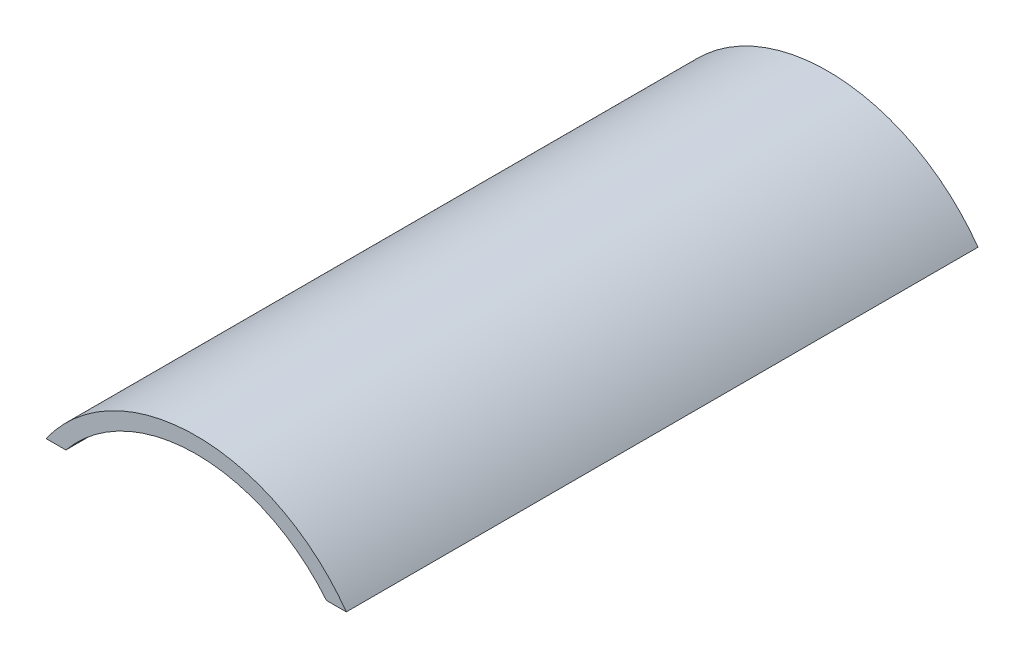
SolidWorks part; units mm, degrees
ref_plane "Front Plane" through (0, 0, 0) normal (0, 0, 1) x (1, 0, 0)
ref_plane "Top Plane" through (0, 0, 0) normal (0, 1, 0) x (1, 0, 0)
ref_plane "Right Plane" through (0, 0, 0) normal (1, 0, 0) x (0, 0, -1)
sketch "Sketch1" plane through (0, 0, 0) normal (0, 0, 1) x (1, 0, 0)
  line L2 (-12.3765, 10.1401) -> (-14.2628, 10.1401)
  line L3 (12.3765, 10.1401) -> (14.2628, 10.1401)
  line L5 (-15.2184, 8.6401) -> (15.2184, 8.6401) construction
  line L6 (-12.3765, 10.1401) -> (12.3765, 10.1401) construction
  arc A0 (12.3765, 10.1401) -> (-12.3765, 10.1401) centre (0, 0) ccw
  arc A1 (14.2628, 10.1401) -> (-14.2628, 10.1401) centre (0, 0) ccw
  arc A2 (15.2184, 8.6401) -> (-15.2184, 8.6401) centre (0, 0) ccw construction
  dimension "D1" = 32
  dimension "D2" = 1.5
extrude "Boss-Extrude1" add sketch "Sketch1" along normal blind 60 contours A1 L2 A0 L3
